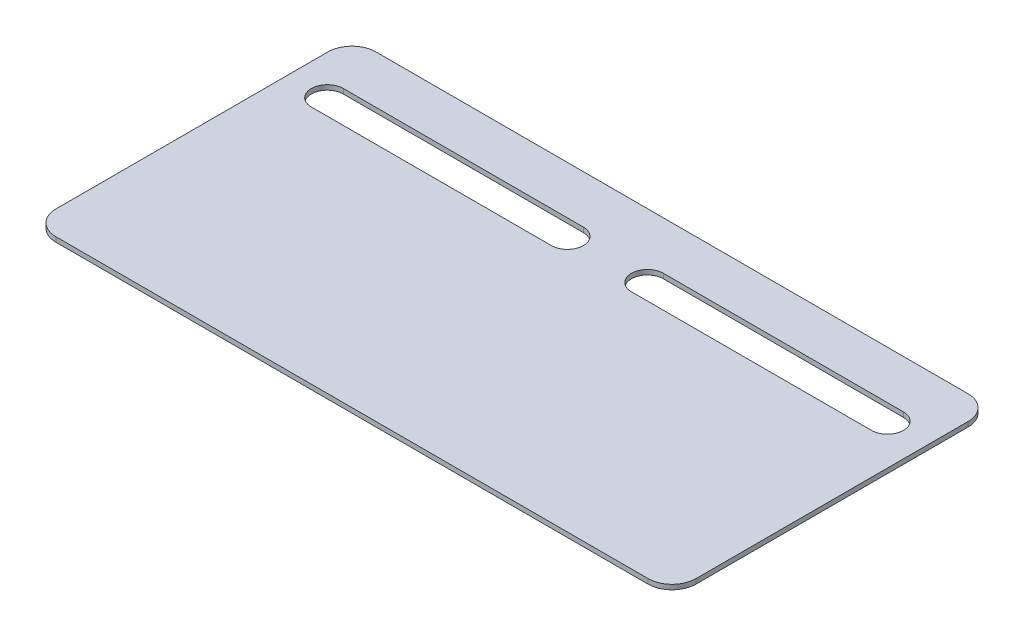
SolidWorks part; units mm, degrees
ref_plane "前视基准面" through (0, 0, 0) normal (0, 0, 1) x (1, 0, 0)
ref_plane "上视基准面" through (0, 0, 0) normal (0, 1, 0) x (1, 0, 0)
ref_plane "右视基准面" through (0, 0, 0) normal (1, 0, 0) x (0, 0, -1)
sketch "草图1" plane through (0, 0, 0) normal (0, 1, 0) x (1, 0, 0)
  line L5 (-184.6157, 100) -> (185.3843, 100)
  line L6 (-199.6157, 85) -> (-199.6157, -85)
  line L11 (-184.6157, -100) -> (185.3843, -100)
  line L12 (200.3843, 85) -> (200.3843, -85)
  line L13 (-199.6157, 100) -> (200.3843, -100) construction
  line L14 (-199.6157, -100) -> (200.3843, 100) construction
  arc A0 (185.3843, 100) -> (200.3843, 85) centre (185.3843, 85) cw
  arc A1 (185.3843, -100) -> (200.3843, -85) centre (185.3843, -85) ccw
  arc A2 (-199.6157, -85) -> (-184.6157, -100) centre (-184.6157, -85) ccw
  arc A3 (-184.6157, 100) -> (-199.6157, 85) centre (-184.6157, 85) ccw
  point P0 (0.3843, 0)
  dimension "D3" = 15
  dimension "D1" = 200
  dimension "D2" = 400
extrude "凸台-拉伸1" add sketch "草图1" along normal blind 3
sketch "草图2" plane through (0, 3, 0) normal (0, 1, 0) x (1, 0, 0)
  line L0 (-175, 60) -> (-25, 60) construction
  line L3 (-175, 70) -> (-25, 70)
  line L6 (-175, 50) -> (-25, 50)
  line L7 (25, 50) -> (175, 50)
  line L8 (25, 70) -> (175, 70)
  line L9 (25, 60) -> (175, 60) construction
  arc A4 (-175, 70) -> (-175, 50) centre (-175, 60) ccw
  arc A5 (-25, 50) -> (-25, 70) centre (-25, 60) ccw
  arc A6 (25, 70) -> (25, 50) centre (25, 60) ccw
  arc A7 (175, 50) -> (175, 70) centre (175, 60) ccw
  point P2 (-100, 60)
  point P7 (0, 0)
  point P9 (0, 0)
  point P11 (100, 60)
  point P16 (0, 0)
  dimension "D1" = 2
extrude "切除-拉伸3" cut sketch "草图2" against normal blind 3
